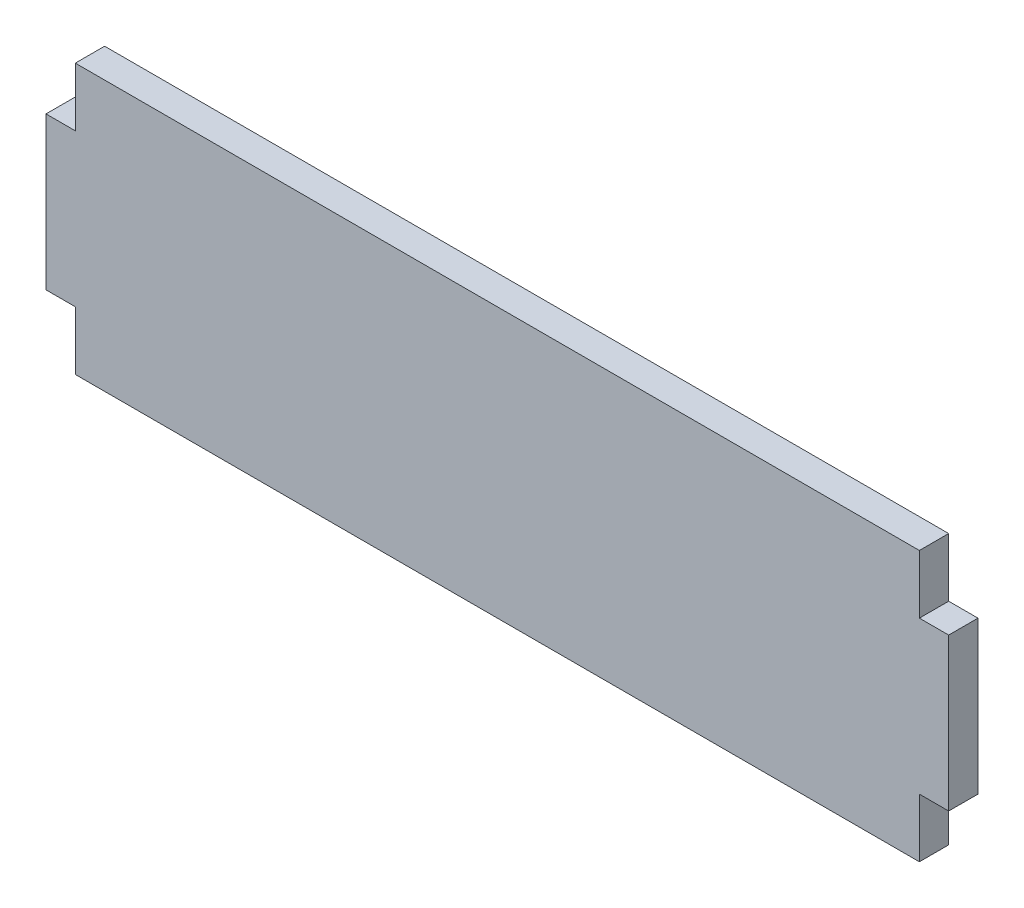
SolidWorks part; units mm, degrees
ref_plane "Plan de face" through (0, 0, 0) normal (0, 0, 1) x (1, 0, 0)
ref_plane "Plan de dessus" through (0, 0, 0) normal (0, 1, 0) x (1, 0, 0)
ref_plane "Plan de droite" through (0, 0, 0) normal (1, 0, 0) x (0, 0, -1)
sketch "Esquisse1" plane through (0, 0, 0) normal (0, 0, 1) x (1, 0, 0)
  line L0 (-72, 23) -> (72, 23)
  line L1 (72, 23) -> (72, -23) construction
  line L2 (72, -23) -> (-72, -23)
  line L3 (-72, -23) -> (-72, 23) construction
  line L4 (0, 0) -> (0, 35.7778) construction
  line L5 (0, 0) -> (72, 0) construction
  line L6 (-72, 23) -> (-72, 13)
  line L7 (-72, 13) -> (-77, 13)
  line L8 (-77, 13) -> (-77, -13)
  line L9 (-77, -13) -> (-72, -13)
  line L10 (-72, -13) -> (-72, -23)
  line L11 (72, -13) -> (72, -23)
  line L12 (77, -13) -> (72, -13)
  line L13 (77, 13) -> (77, -13)
  line L14 (72, 13) -> (77, 13)
  line L15 (72, 23) -> (72, 13)
  circle A0 centre (0, 0) radius 5 construction
  circle A1 centre (12, 0) radius 5 construction
  circle A2 centre (0, 12) radius 5 construction
  point P13 (0, 0)
  dimension "D4" = 10
  dimension "D5" = 10
  dimension "D7" = 10
  dimension "D1" = 144
  dimension "D2" = 26
  dimension "D3" = 46
  dimension "D6" = 12
  dimension "D8" = 12
  dimension "10" = 10
  dimension "D10" = 5
extrude "Boss.-Extru.1" add sketch "Esquisse1" along normal blind 5
